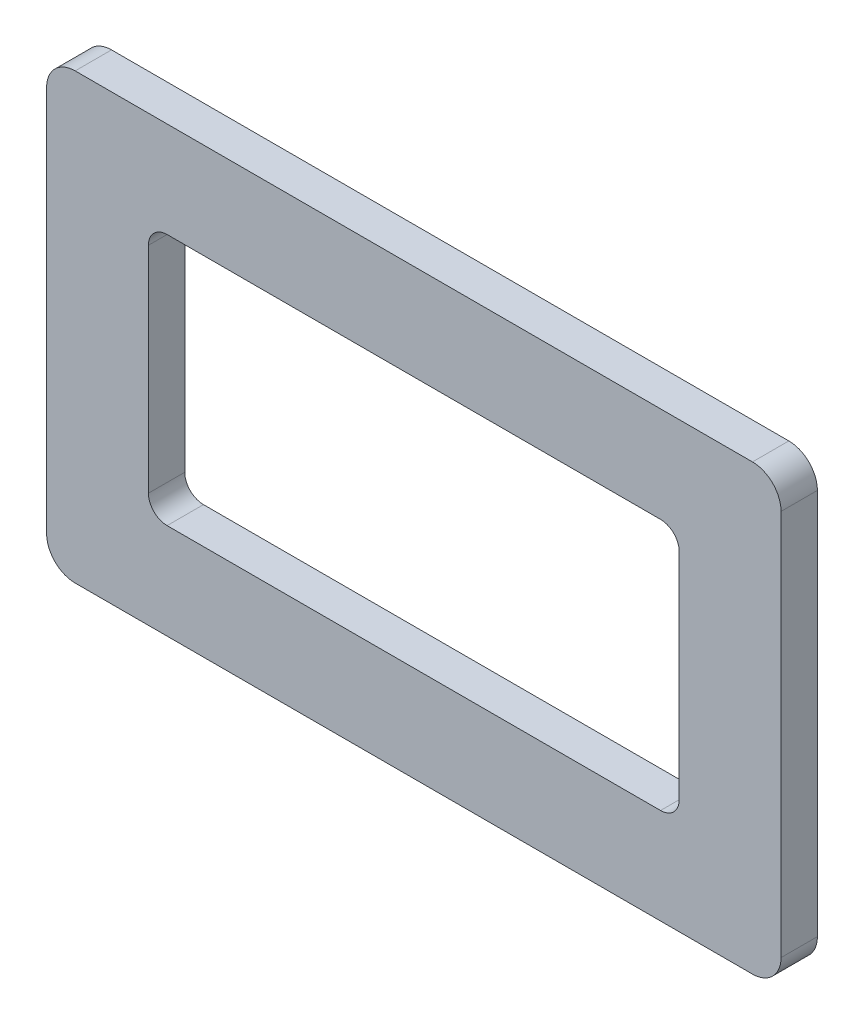
SolidWorks part; units mm, degrees
ref_plane "Front Plane" through (0, 0, 0) normal (0, 0, 1) x (1, 0, 0)
ref_plane "Top Plane" through (0, 0, 0) normal (0, 1, 0) x (1, 0, 0)
ref_plane "Right Plane" through (0, 0, 0) normal (1, 0, 0) x (0, 0, -1)
sketch "Sketch1" plane through (0, 0, 0) normal (0, 0, 1) x (1, 0, 0)
  line L1 (-35.35, 21.35) -> (35.35, 21.35)
  line L2 (-35.35, 21.35) -> (-35.35, -21.35)
  line L3 (-35.35, -21.35) -> (35.35, -21.35)
  line L4 (35.35, 21.35) -> (35.35, -21.35)
  line L5 (-35.35, 21.35) -> (35.35, -21.35) construction
  line L6 (-35.35, -21.35) -> (35.35, 21.35) construction
  line L7 (-25.55, 12.1343) -> (25.55, 12.1343)
  line L8 (-25.55, 12.1343) -> (-25.55, -12.1343)
  line L9 (-25.55, -12.1343) -> (25.55, -12.1343)
  line L10 (25.55, 12.1343) -> (25.55, -12.1343)
  line L11 (-25.55, 12.1343) -> (25.55, -12.1343) construction
  line L12 (-25.55, -12.1343) -> (25.55, 12.1343) construction
  point P0 (0, 0)
  point P6 (0, 0)
  dimension "D1" = 70.7
  dimension "D2" = 42.7
  dimension "D3" = 9.8
extrude "Boss-Extrude1" add sketch "Sketch1" along normal blind 3.5
fillet "Fillet1" radius 2.75 4 edges at (-35.35, -21.35, 1.75) (35.35, -21.35, 1.75) (35.35, 21.35, 1.75) (-35.35, 21.35, 1.75)
fillet "Fillet2" radius 1.8 4 edges at (25.55, -12.1343, 1.75) (-25.55, -12.1343, 1.75) (-25.55, 12.1343, 1.75) (25.55, 12.1343, 1.75)
